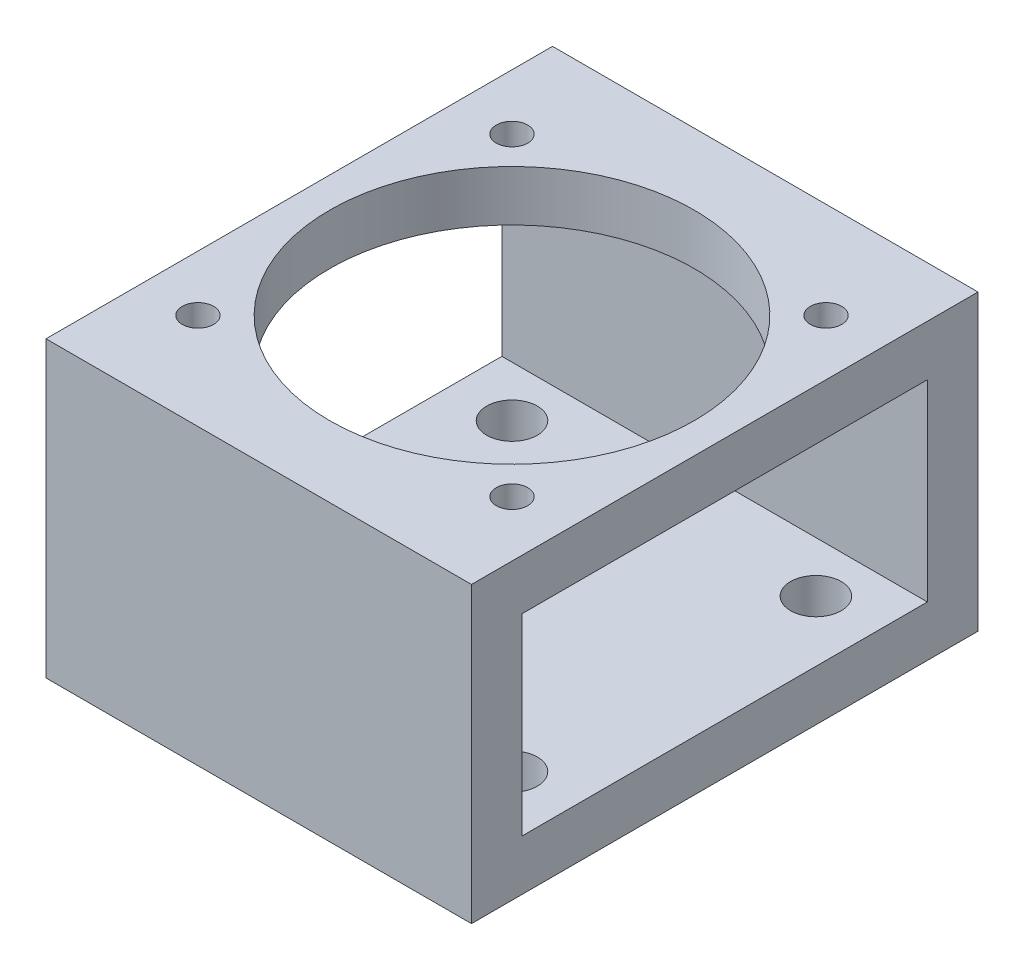
SolidWorks part; units mm, degrees
ref_plane "Front Plane" through (0, 0, 0) normal (0, 0, 1) x (1, 0, 0)
ref_plane "Top Plane" through (0, 0, 0) normal (0, 1, 0) x (1, 0, 0)
ref_plane "Right Plane" through (0, 0, 0) normal (1, 0, 0) x (0, 0, -1)
sketch "Sketch1" plane through (0, 0, 0) normal (0, 1, 0) x (1, 0, 0)
  line L1 (-21, -25) -> (21, -25)
  line L2 (-21, -25) -> (-21, 25)
  line L3 (-21, 25) -> (21, 25)
  line L4 (21, -25) -> (21, 25)
  line L5 (-21, -25) -> (21, 25) construction
  line L6 (-21, 25) -> (21, -25) construction
  point P0 (0, 0)
  dimension "D1" = 50
  dimension "D2" = 42
extrude "Boss-Extrude1" add sketch "Sketch1" along normal blind 8
sketch "Sketch2" plane through (0, 8, 0) normal (0, 1, 0) x (1, 0, 0)
  line L1 (15.5, -15.5) -> (-15.5, -15.5) construction
  line L2 (15.5, -15.5) -> (15.5, 15.5) construction
  line L3 (15.5, 15.5) -> (-15.5, 15.5) construction
  line L4 (-15.5, -15.5) -> (-15.5, 15.5) construction
  line L5 (15.5, -15.5) -> (-15.5, 15.5) construction
  line L6 (15.5, 15.5) -> (-15.5, -15.5) construction
  circle A0 centre (-15.5, 15.5) radius 1.55
  circle A1 centre (15.5, 15.5) radius 1.55
  circle A2 centre (15.5, -15.5) radius 1.55
  circle A3 centre (-15.5, -15.5) radius 1.55
  circle A4 centre (0, 0) radius 18
  point P0 (0, 0)
  point P16 (0, 0)
  dimension "D3" = 3.1
  dimension "D5" = 36
  dimension "D1" = 31
  dimension "D2" = 31
  dimension "D4" = 4
extrude "Cut-Extrude1" cut sketch "Sketch2" against normal up to next
sketch "Sketch3" plane through (0, 0, 0) normal (0, 1, 0) x (1, 0, 0)
  line L1 (21, -25) -> (-21, -25)
  line L2 (21, -25) -> (21, 25)
  line L3 (21, 25) -> (-21, 25)
  line L4 (-21, -25) -> (-21, 25)
  line L5 (21, -25) -> (-21, 25) construction
  line L6 (21, 25) -> (-21, -25) construction
  point P0 (0, 0)
  point P13 (0, 0)
extrude "Boss-Extrude2" add sketch "Sketch3" against normal blind 21
sketch "Sketch4" plane through (-21, 0, 0) normal (-1, 0, 0) x (0, 0, 1)
  line L0 (0, -6.5) -> (0, 0) construction
  line L4 (-20, 3) -> (20, 3)
  line L5 (-20, 3) -> (-20, -16)
  line L6 (-20, -16) -> (20, -16)
  line L7 (20, 3) -> (20, -16)
  line L8 (-20, 3) -> (20, -16) construction
  line L9 (-20, -16) -> (20, 3) construction
  line L10 (-25, 8) -> (25, 8) construction
  line L11 (-25, -21) -> (25, -21) construction
  line L12 (25, 8) -> (25, -21) construction
  point P6 (0, -6.5)
  dimension "D1" = 5
  dimension "D2" = 5
  dimension "D3" = 5
extrude "Cut-Extrude2" cut sketch "Sketch4" against normal up to next
sketch "Sketch6" plane through (0, -21, 0) normal (0, -1, 0) x (-1, 0, 0)
  line L0 (-21, 0) -> (21, 0) construction
  line L1 (21, 25) -> (21, -25) construction
  circle A0 centre (-15, 15) radius 2.5
  circle A1 centre (15, 15) radius 2.5
  circle A2 centre (15, -15) radius 2.5
  circle A3 centre (-15, -15) radius 2.5
  point P8 (0, 0)
  dimension "D1" = 5
  dimension "D2" = 15
  dimension "D3" = 15
  dimension "D4" = 2
  dimension "D5" = 2
extrude "Cut-Extrude3" cut sketch "Sketch6" against normal up to next
